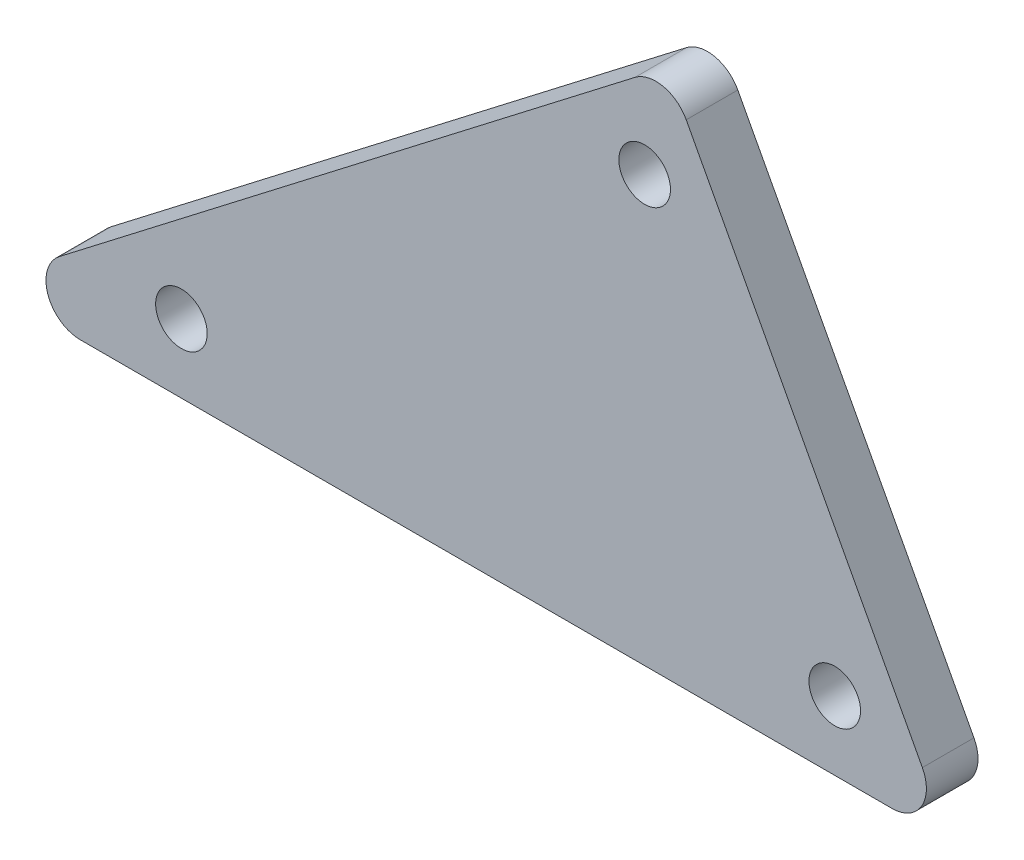
SolidWorks part; units mm, degrees
material "ABS"
ref_plane "Plan de face" through (0, 0, 0) normal (0, 0, 1) x (1, 0, 0)
ref_plane "Plan de dessus" through (0, 0, 0) normal (0, 1, 0) x (1, 0, 0)
ref_plane "Plan de droite" through (0, 0, 0) normal (1, 0, 0) x (0, 0, -1)
sketch "Esquisse1" plane through (0, 0, 0) normal (0, 0, 1) x (1, 0, 0)
  line L0 (0, 0) -> (-38, 0)
  line L1 (-38, 0) -> (-11.0559, 20.7368)
  line L2 (-11.0559, 20.7368) -> (0, 0)
  line L3 (-49.7557, -4) -> (-9.7499, 26.7895)
  line L4 (-9.7499, 26.7895) -> (6.6656, -4)
  line L5 (6.6656, -4) -> (-49.7557, -4)
  circle A0 centre (-11.0559, 20.7368) radius 1.5
  circle A1 centre (-38, 0) radius 1.5
  circle A2 centre (0, 0) radius 1.5
  dimension "D4" = 3
  dimension "D5" = 3
  dimension "D6" = 3
  dimension "D1" = 38
  dimension "D2" = 34
  dimension "D3" = 23.5
  dimension "D7" = 4
extrude "Boss.-Extru.1" add sketch "Esquisse1" along normal blind 3 contours L5 L4 L3 A2 L0 A1 L1 A0 L2 | A2 L2 A0 L1 A1 L0
fillet "Congé2" radius 2 3 edges at (-49.7557, -4, 1.5) (6.6656, -4, 1.5) (-9.7499, 26.7895, 1.5)
